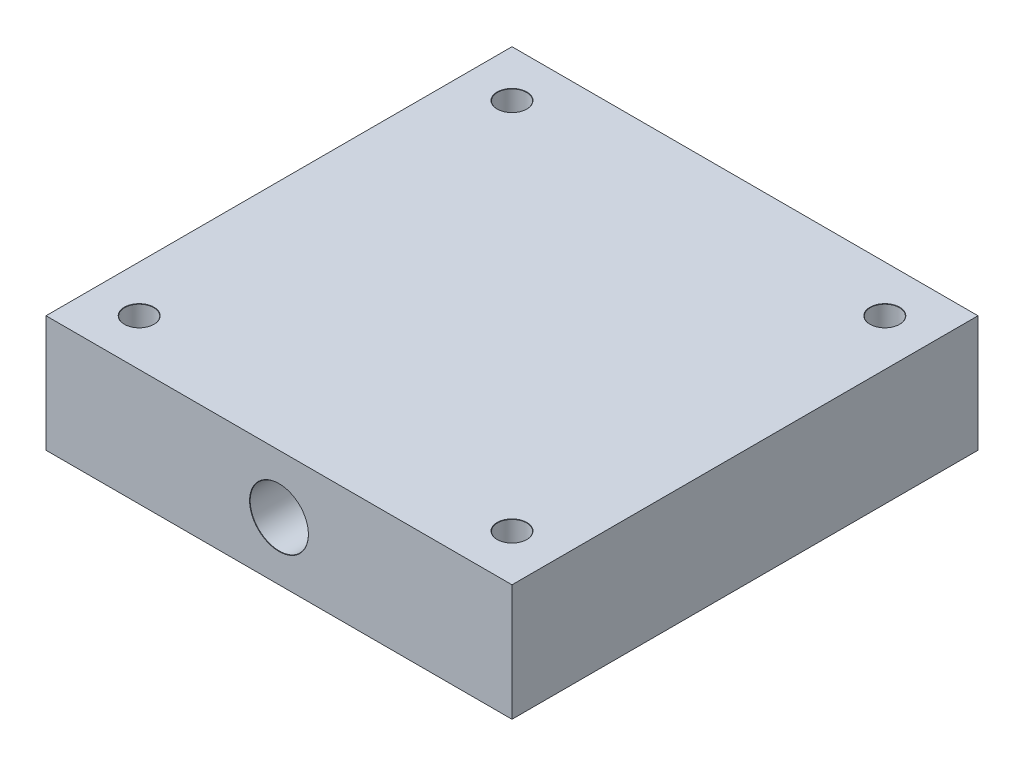
SolidWorks part; units mm, degrees
ref_plane "Plan de face" through (0, 0, 0) normal (0, 0, 1) x (1, 0, 0)
ref_plane "Plan de dessus" through (0, 0, 0) normal (0, 1, 0) x (1, 0, 0)
ref_plane "Plan de droite" through (0, 0, 0) normal (1, 0, 0) x (0, 0, -1)
sketch "Esquisse1" plane through (0, 0, 0) normal (0, 1, 0) x (1, 0, 0)
  line L1 (0, 0) -> (40, 0)
  line L2 (0, 0) -> (0, 40)
  line L3 (0, 40) -> (40, 40)
  line L4 (40, 0) -> (40, 40)
  dimension "D1" = 40
  dimension "D2" = 40
extrude "Boss.-Extru.1" add sketch "Esquisse1" along normal blind 10
sketch "Esquisse4" plane through (0, 0, 0) normal (0, 0, 1) x (1, 0, 0)
  line L0 (0, 10) -> (40, 10) construction
  line L1 (40, 10) -> (40, 0) construction
  circle A0 centre (20, 5) radius 2
  dimension "D1" = 4
  dimension "D2" = 5
  dimension "D3" = 20
hole_wizard "Diamètre du perçage Ø4.0 (4)1" positions "Esquisse6" profile "Esquisse5" hole size "Ø4.0" standard "ISO" end condition through all
sketch "Esquisse6" plane through (0, 0, 0) normal (0, 0, 1) x (1, 0, 0)
  point P0 (20, 5)
sketch "Esquisse5" plane through (20, 5, 0) normal (1, 0, 0) x (0, -1, 0)
  line L0 (0, 0) -> (0, 40)
  line L1 (0, 40) -> (2, 40)
  line L2 (2, 40) -> (2, 0)
  line L5 (2, 0) -> (0, 0)
  line L11 (0, -6.35) -> (0, 107.95) construction
  dimension "Diamètre du perçage jusqu'au prochain" = 4
  dimension "Profondeur du perçage jusqu'au prochain" = 40
sketch "Esquisse2" plane through (0, 0, 0) normal (0, 0, 1) x (1, 0, 0)
  line L0 (40, 10) -> (40, 0) construction
  line L1 (0, 10) -> (40, 10) construction
  circle A0 centre (20, 5) radius 3
  dimension "D1" = 6
  dimension "D2" = 20
  dimension "D3" = 5
hole_wizard "Trou pour taraudage pour trou taraudé M61" positions "Esquisse8" profile "Esquisse9" hole size "M6" standard "ISO"
sketch "Esquisse8" plane through (0, 0, 0) normal (0, 0, 1) x (1, 0, 0)
  point P0 (20, 5)
sketch "Esquisse9" plane through (20, 5, 0) normal (1, 0, 0) x (0, -1, 0)
  line L0 (0, 0) -> (0, 9.5022)
  line L1 (0, 9.5022) -> (2.5, 8)
  line L2 (2.5, 8) -> (2.5, 0.025)
  line L3 (2.5, 0.025) -> (2.525, 0)
  line L5 (2.525, 0) -> (0, 0)
  line L6 (-2.5, 0.025) -> (-2.525, 0) construction
  line L10 (0, 9.5022) -> (-2.5, 8) construction
  line L11 (0, -6.35) -> (0, 107.95) construction
  dimension "Diamètre du perçage" = 5
  dimension "Profondeur du perçage" = 8
  dimension "Diamètre du fraisage entrant" = 5.05
  dimension "Angle du fraisage entrant" = 90
  dimension "Angle de pointe" = 118
sketch "Esquisse3" plane through (0, 0, -40) normal (0, 0, -1) x (-1, 0, 0)
  line L0 (-40, 10) -> (-40, 0) construction
  line L1 (-40, 10) -> (0, 10) construction
  circle A0 centre (-20, 5) radius 3
  dimension "D1" = 6
  dimension "D2" = 20
  dimension "D3" = 5
hole_wizard "Diamètre du perçage Ø6.0 (6)1" positions "Esquisse11" profile "Esquisse12" hole size "Ø6.0" standard "ISO"
sketch "Esquisse11" plane through (0, 0, -40) normal (0, 0, -1) x (-1, 0, 0)
  point P0 (-20, 5)
sketch "Esquisse12" plane through (20, 5, -40) normal (1, 0, 0) x (0, 1, 0)
  line L0 (0, 0) -> (0, 21.8026)
  line L1 (0, 21.8026) -> (3, 20)
  line L2 (3, 20) -> (3, 0)
  line L5 (3, 0) -> (0, 0)
  line L10 (0, 21.8026) -> (-3, 20) construction
  line L11 (0, -6.35) -> (0, 107.95) construction
  dimension "Diamètre du perçage" = 6
  dimension "Profondeur du perçage" = 20
  dimension "Angle de pointe" = 118
sketch "Esquisse16" plane through (0, 0, 0) normal (0, -1, 0) x (1, 0, 0)
  line L0 (0, 0) -> (40, 0) construction
  line L1 (0, -40) -> (0, 0) construction
  line L2 (40, 0) -> (40, -40) construction
  line L3 (40, -40) -> (0, -40) construction
  circle A0 centre (4, -4) radius 1.5
  circle A1 centre (36, -4) radius 1.5
  circle A2 centre (36, -36) radius 1.5
  circle A3 centre (4, -36) radius 1.5
  circle A4 centre (20, -36) radius 1.5
  dimension "D3" = 3
  dimension "D6" = 3
  dimension "D7" = 3
  dimension "D10" = 3
  dimension "D11" = 20
  dimension "D15" = 3
  dimension "D1" = 4
  dimension "D2" = 4
  dimension "D4" = 4
  dimension "D5" = 4
  dimension "D8" = 4
  dimension "D9" = 4
  dimension "D12" = 4
  dimension "D13" = 4
  dimension "D14" = 4
hole_wizard "Trou pour taraudage pour trou taraudé M31" positions "Esquisse18" profile "Esquisse17" hole size "M3" standard "ISO" end condition through all
sketch "Esquisse18" plane through (0, 0, 0) normal (0, -1, 0) x (-1, 0, 0)
  point P0 (-4, 4)
  point P3 (-36, 4)
  point P6 (-36, 36)
  point P9 (-4, 36)
sketch "Esquisse17" plane through (4, 0, -4) normal (1, 0, 0) x (0, 0, -1)
  line L0 (0, 0) -> (0, 10)
  line L1 (0, 10) -> (1.275, 10)
  line L2 (1.25, 9.975) -> (1.25, 0.025)
  line L3 (1.25, 0.025) -> (1.275, 0)
  line L5 (1.275, 0) -> (0, 0)
  line L6 (-1.25, 0.025) -> (-1.275, 0) construction
  line L7 (1.275, 10) -> (1.25, 9.975)
  line L8 (-1.275, 10) -> (-1.25, 9.975) construction
  line L11 (0, -6.35) -> (0, 107.95) construction
  dimension "Diamètre du perçage jusqu'au prochain" = 2.5
  dimension "Profondeur du perçage jusqu'au prochain" = 10
  dimension "Diamètre du fraisage entrant" = 2.55
  dimension "Angle du fraisage entrant" = 90
  dimension "Diamètre du fraisage débouchant" = 2.55
  dimension "Angle du fraisage débouchant" = 90
hole_wizard "Trou pour taraudage pour trou taraudé M32" positions "Esquisse20" profile "Esquisse19" hole size "M3" standard "ISO"
sketch "Esquisse20" plane through (0, 0, 0) normal (0, -1, 0) x (-1, 0, 0)
  point P0 (-20, 36)
sketch "Esquisse19" plane through (20, 0, -36) normal (1, 0, 0) x (0, 0, -1)
  line L0 (0, 0) -> (0, 5.7511)
  line L1 (0, 5.7511) -> (1.25, 5)
  line L2 (1.25, 5) -> (1.25, 0.025)
  line L3 (1.25, 0.025) -> (1.275, 0)
  line L5 (1.275, 0) -> (0, 0)
  line L6 (-1.25, 0.025) -> (-1.275, 0) construction
  line L10 (0, 5.7511) -> (-1.25, 5) construction
  line L11 (0, -6.35) -> (0, 107.95) construction
  dimension "Diamètre du perçage" = 2.5
  dimension "Profondeur du perçage" = 5
  dimension "Diamètre du fraisage entrant" = 2.55
  dimension "Angle du fraisage entrant" = 90
  dimension "Angle de pointe" = 118
sketch "Esquisse21" plane through (0, 0, 0) normal (0, -1, 0) x (1, 0, 0)
  line L0 (0, -40) -> (0, 0) construction
  line L1 (0, -8) -> (15, -8)
  line L2 (0, -8) -> (0, -9.6)
  line L3 (0, -9.6) -> (15, -9.6)
  line L4 (15, -8) -> (15, -9.6)
  line L5 (0, 0) -> (40, 0) construction
  line L6 (40, 0) -> (40, -40) construction
  line L7 (40, -8) -> (25, -8)
  line L8 (40, -8) -> (40, -9.6)
  line L9 (40, -9.6) -> (25, -9.6)
  line L10 (25, -8) -> (25, -9.6)
  dimension "D1" = 1.6
  dimension "D2" = 15
  dimension "D3" = 8
  dimension "D4" = 1.6
  dimension "D5" = 8
  dimension "D6" = 15
extrude "Enlèv. mat.-Extru.1" [suppressed] cut sketch "Esquisse21" against normal through all
pattern_linear "Répétition linéaire1" [suppressed] count 8 spacing 3.2
chamfer "Chanfrein1" [suppressed] distance 0.5 angle 45
